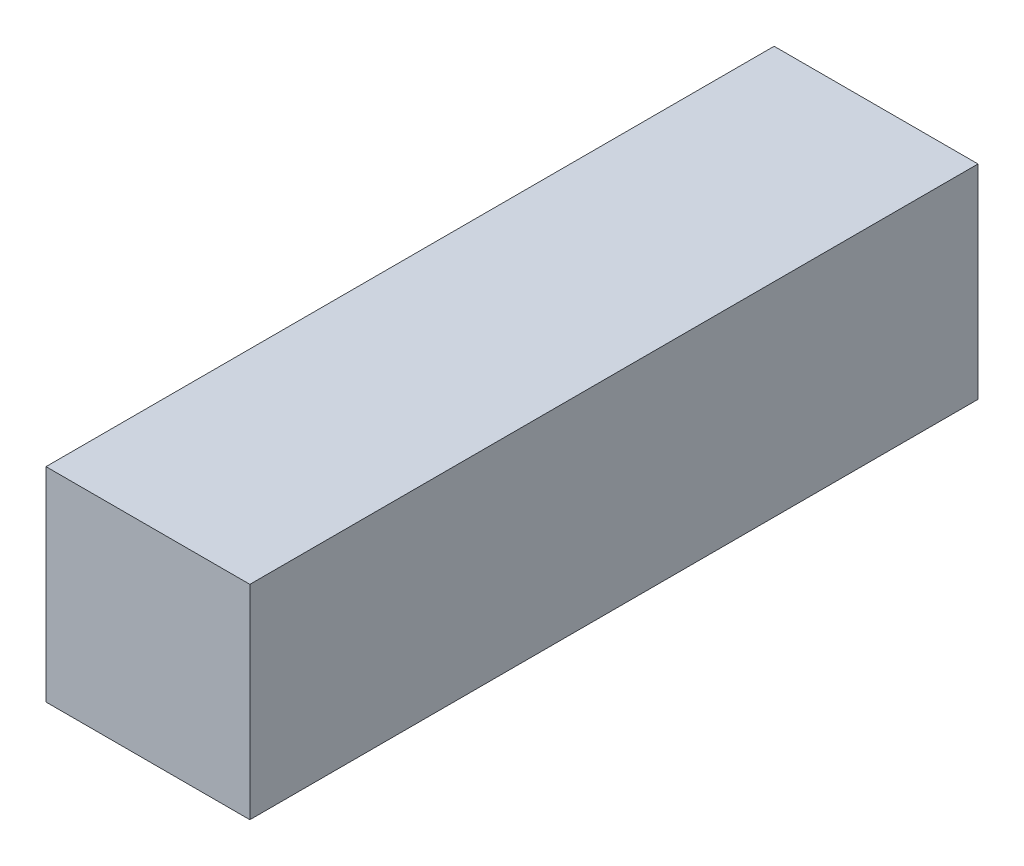
SolidWorks part; units mm, degrees
material "AISI 4340 Steel, annealed"
ref_plane "Front Plane" through (0, 0, 0) normal (0, 0, 1) x (1, 0, 0)
ref_plane "Top Plane" through (0, 0, 0) normal (0, 1, 0) x (1, 0, 0)
ref_plane "Right Plane" through (0, 0, 0) normal (1, 0, 0) x (0, 0, -1)
sketch "Sketch1" plane through (0, 0, 0) normal (0, 0, 1) x (1, 0, 0)
  line L1 (-35, -35) -> (35, -35)
  line L2 (-35, -35) -> (-35, 35)
  line L3 (-35, 35) -> (35, 35)
  line L4 (35, -35) -> (35, 35)
  line L5 (-35, -35) -> (35, 35) construction
  line L6 (-35, 35) -> (35, -35) construction
  point P0 (0, 0)
  dimension "D1" = 70
extrude "Boss-Extrude1" add sketch "Sketch1" against normal blind 250
